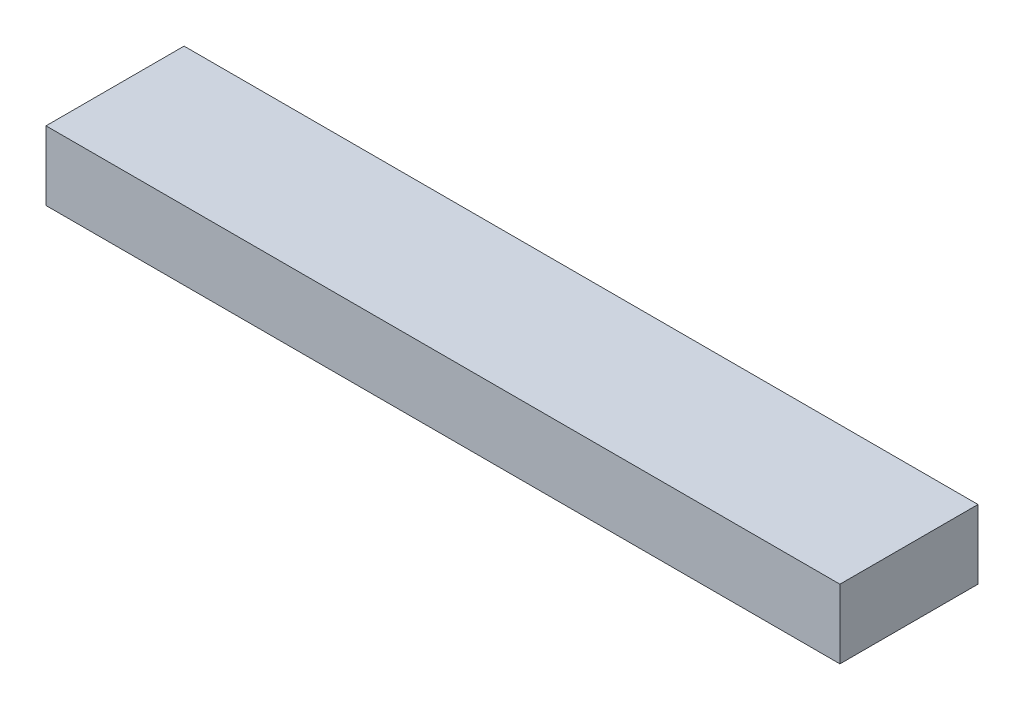
SolidWorks part; units mm, degrees
ref_plane "Front Plane" through (0, 0, 0) normal (0, 0, 1) x (1, 0, 0)
ref_plane "Top Plane" through (0, 0, 0) normal (0, 1, 0) x (1, 0, 0)
ref_plane "Right Plane" through (0, 0, 0) normal (1, 0, 0) x (0, 0, -1)
sketch "Sketch1" plane through (0, 0, 0) normal (0, 1, 0) x (1, 0, 0)
  line L1 (-11.5, 2) -> (11.5, 2)
  line L2 (-11.5, 2) -> (-11.5, -2)
  line L3 (-11.5, -2) -> (11.5, -2)
  line L4 (11.5, 2) -> (11.5, -2)
  line L5 (-11.5, 2) -> (11.5, -2) construction
  line L6 (-11.5, -2) -> (11.5, 2) construction
  point P0 (0, 0)
  dimension "D1" = 23
  dimension "D2" = 4
extrude "Boss-Extrude1" add sketch "Sketch1" along normal blind 2
